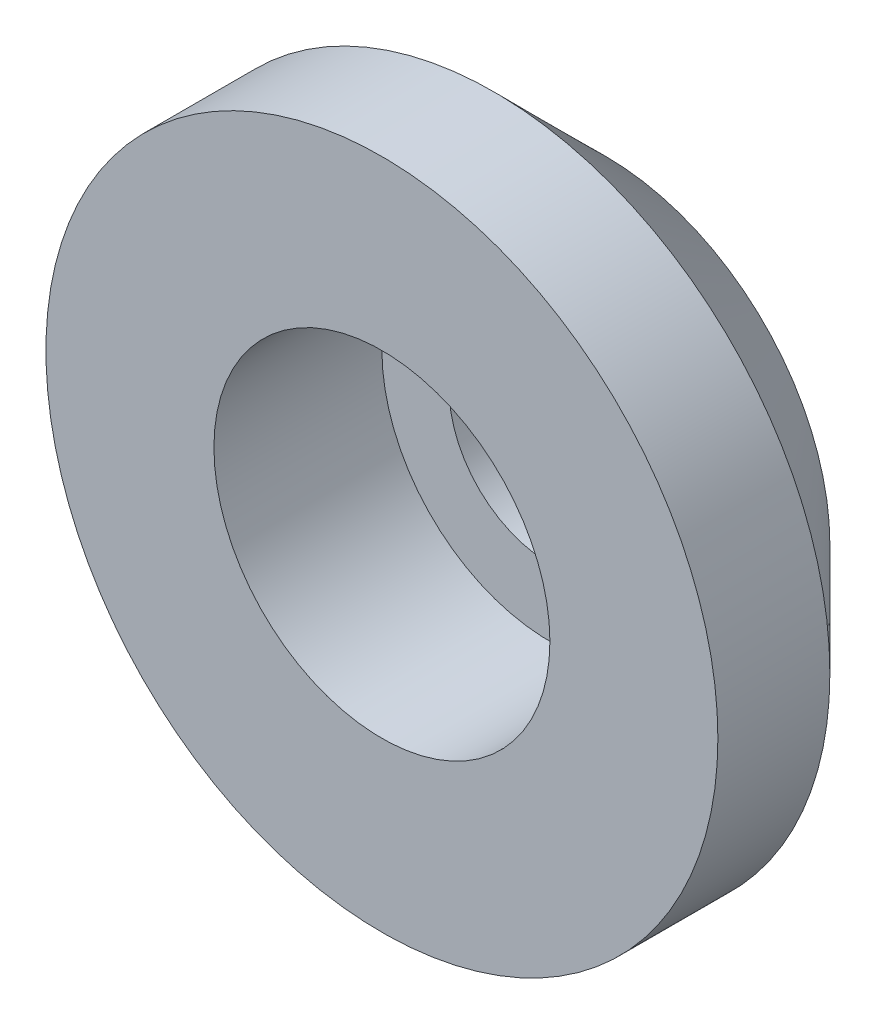
SolidWorks part; units mm, degrees
ref_plane "Front Plane" through (0, 0, 0) normal (0, 0, 1) x (1, 0, 0)
ref_plane "Top Plane" through (0, 0, 0) normal (0, 1, 0) x (1, 0, 0)
ref_plane "Right Plane" through (0, 0, 0) normal (1, 0, 0) x (0, 0, -1)
sketch "Sketch1" plane through (0, 0, 0) normal (0, 0, 1) x (1, 0, 0)
  circle A0 centre (0, 0) radius 0.9
  circle A1 centre (0, 0) radius 3
  dimension "D1" = 1.8
  dimension "D2" = 6
extrude "Boss-Extrude1" add sketch "Sketch1" along normal blind 2
chamfer "Chamfer1" distance 1 angle 45 1 edges at (3, 0, 0)
sketch "Sketch2" plane through (0, 0, 2) normal (0, 0, 1) x (1, 0, 0)
  circle A0 centre (0, 0) radius 1.5
  dimension "D1" = 3
extrude "Cut-Extrude1" cut sketch "Sketch2" against normal blind 1.5
